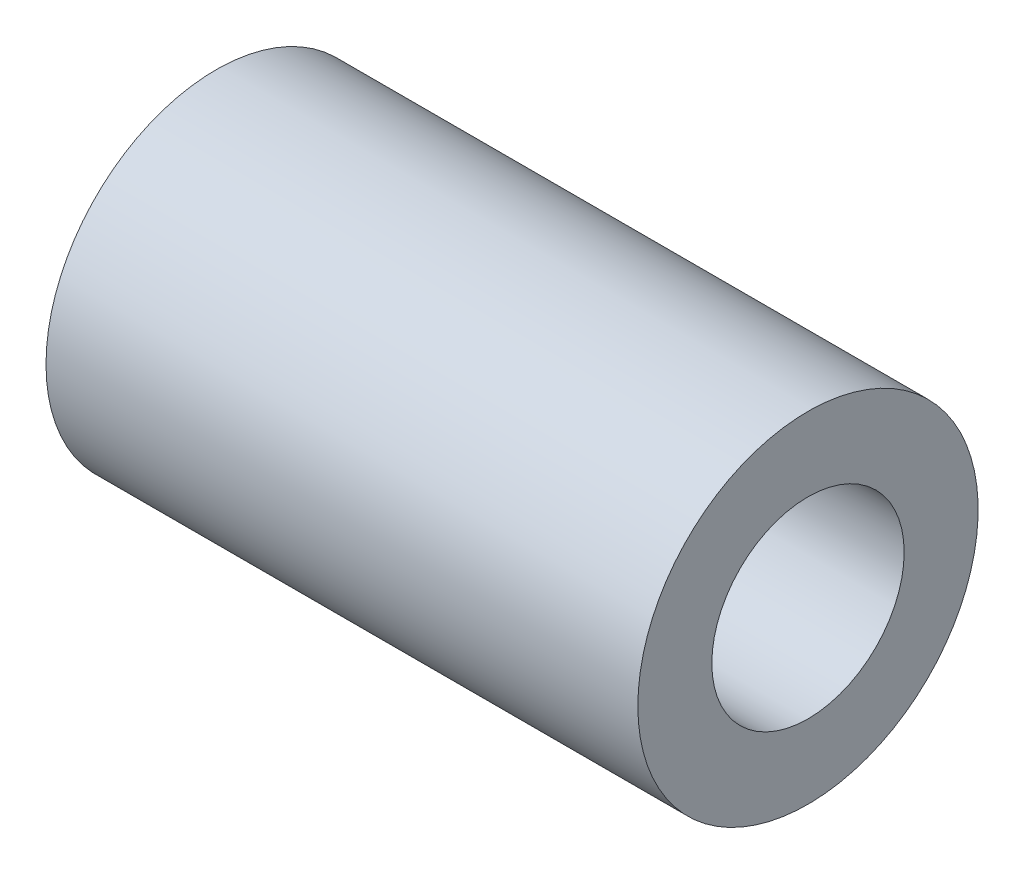
SolidWorks part; units mm, degrees
ref_plane "Front" through (0, 0, 0) normal (0, 0, 1) x (1, 0, 0)
ref_plane "Top" through (0, 0, 0) normal (0, 1, 0) x (1, 0, 0)
ref_plane "Right" through (0, 0, 0) normal (1, 0, 0) x (0, 0, -1)
sketch "Sketch1" plane through (0, 0, 0) normal (0, 0, 1) x (1, 0, 0)
  line L0 (-12.23, 0) -> (30.0526, 0) construction
  line L1 (0, 0) -> (24, 0)
  line L2 (0, 6.9) -> (24, 6.9)
  line L3 (0, 6.9) -> (0, 0)
  line L5 (24, 6.9) -> (24, 0)
  dimension "D2" = 13.8
  dimension "D3" = 24
revolve "Revolve1" add sketch "Sketch1" angle 360 about L0
hole_wizard "Ø7.8 (7.8) Diameter Hole1" positions "Sketch3" profile "Sketch2" hole size "Ø7.8" standard "JIS" end condition through all
sketch "Sketch3" plane through (0, 0, 0) normal (-1, 0, 0) x (0, 0, 1)
  point P1 (0, 0)
sketch "Sketch2" plane through (0, 0, 0) normal (0, 1, 0) x (0, 0, 1)
  line L0 (0, 0) -> (0, 24)
  line L1 (0, 24) -> (3.9, 24)
  line L2 (3.9, 24) -> (3.9, 0)
  line L5 (3.9, 0) -> (0, 0)
  line L11 (0, -6.35) -> (0, 107.95) construction
  dimension "Thru Hole Dia." = 7.8
  dimension "Thru Hole Depth" = 24
